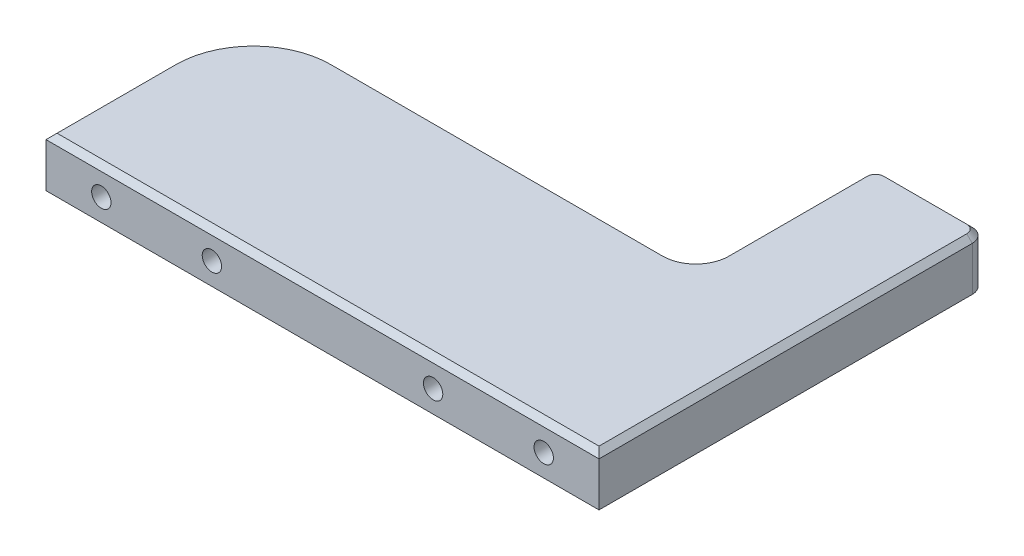
SolidWorks part; units mm, degrees
material "6061 Alloy"
ref_plane "Front Plane" through (0, 0, 0) normal (0, 0, 1) x (1, 0, 0)
ref_plane "Top Plane" through (0, 0, 0) normal (0, 1, 0) x (1, 0, 0)
ref_plane "Right Plane" through (0, 0, 0) normal (1, 0, 0) x (0, 0, -1)
sketch "Sketch1" plane through (0, 0, 0) normal (0, 1, 0) x (1, 0, 0)
  line L0 (0, 0) -> (0, -140)
  line L1 (0, 0) -> (-40, 0)
  line L3 (-40, 0) -> (-40, -65)
  line L5 (-40, -65) -> (-200, -65)
  line L6 (-200, -65) -> (-200, -140)
  line L7 (-200, -140) -> (0, -140)
  dimension "D1" = 40
  dimension "D2" = 140
  dimension "D3" = 200
  dimension "D4" = 75
extrude "Boss-Extrude1" add sketch "Sketch1" along normal blind 20
fillet "Fillet1" radius 10 1 edges at (-40, 10, 65)
hole_wizard "M6 Clearance Hole1" positions "Sketch4" profile "Sketch5" hole size "M6" standard "DIN"
sketch "Sketch4" plane through (10895.2748, -492.9977, 140) normal (0, 0, 1) x (1, 0, 0)
  point P0 (-11075.2748, 502.9977)
  point P1 (-11035.2748, 502.9977)
  point P2 (-10955.2748, 502.9977)
  point P3 (-10915.2748, 502.9977)
sketch "Sketch5" plane through (-180, 10, 140) normal (1, 0, 0) x (0, -1, 0)
  line L0 (0, 0) -> (0, 40)
  line L1 (0, 40) -> (3.5, 40)
  line L2 (3.5, 40) -> (3.5, 0)
  line L3 (3.5, 0) -> (0, 0)
  line L4 (0, -6.35) -> (0, 107.95) construction
  dimension "Thru Hole Dia." = 7
  dimension "Thru Hole Depth" = 40
fillet "Fillet2" radius 5 2 edges at (0, 10, 0) (-40, 10, 0)
fillet "Fillet3" radius 30 1 edges at (-200, 10, 65)
fillet "Chamfer1" radius 2 20 edges at (-200, 0, 117.5) (-191.2132, 0, 73.7868) (-110, 0, 65) (-42.9289, 0, 62.0711) (-40, 0, 30) (-38.5355, 0, 1.4645) (-20, 0, 0) (-1.4645, 0, 1.4645) (0, 0, 72.5) (-100, 0, 140) (-42.9289, 20, 62.0711) (-40, 20, 30) (-38.5355, 20, 1.4645) (-20, 20, 0) (-1.4645, 20, 1.4645) (0, 20, 72.5) (-100, 20, 140) (-200, 20, 117.5) (-191.2132, 20, 73.7868) (-110, 20, 65) profile chamfer
